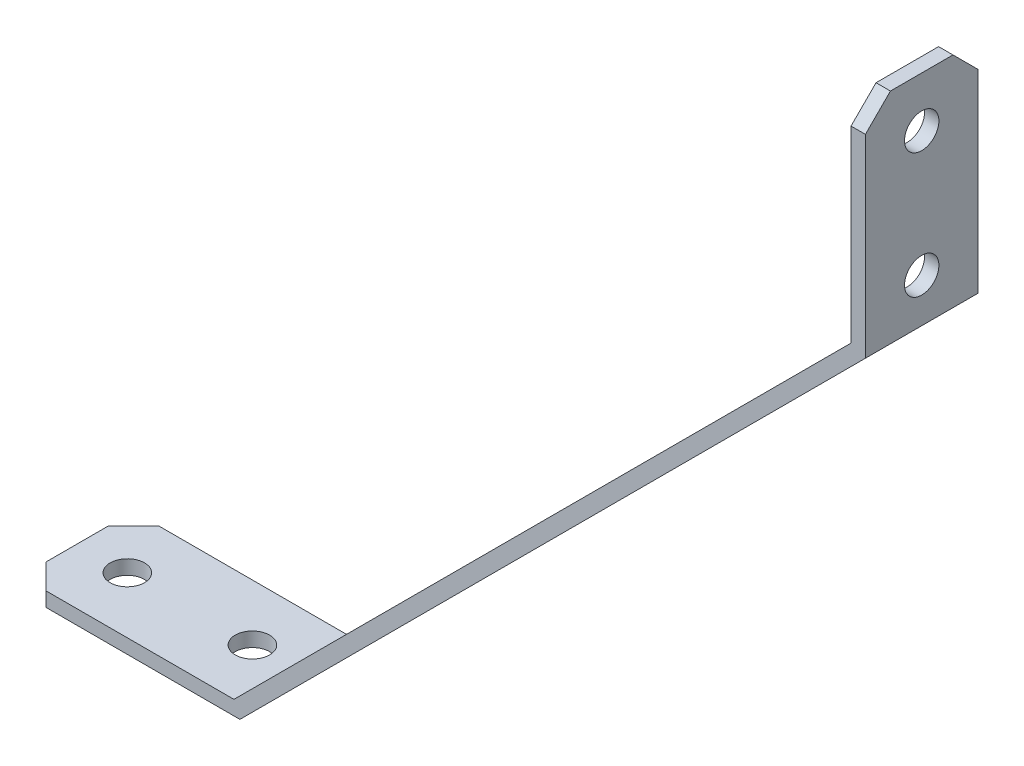
SolidWorks part; units mm, degrees
material "1023 Carbon Steel Sheet (SS)"
ref_plane "Front Plane" through (0, 0, 0) normal (0, 0, 1) x (1, 0, 0)
ref_plane "Top Plane" through (0, 0, 0) normal (0, 1, 0) x (1, 0, 0)
ref_plane "Right Plane" through (0, 0, 0) normal (1, 0, 0) x (0, 0, -1)
sketch "Sketch1" plane through (0, 0, 0) normal (0, 0, 1) x (1, 0, 0)
  line L0 (0, 0) -> (35, 0)
  line L1 (35, 0) -> (135, 100)
  line L2 (135, 100) -> (135, 135)
  line L3 (135, 135) -> (132.7, 135)
  line L4 (132.7, 135) -> (132.7, 100.9527)
  line L5 (132.7, 100.9527) -> (34.0473, 2.3)
  line L6 (34.0473, 2.3) -> (0, 2.3)
  line L7 (0, 2.3) -> (0, 0)
  dimension "D1" = 2.3
  dimension "D2" = 2.3
  dimension "D3" = 35
  dimension "D4" = 2.3
  dimension "D5" = 35
  dimension "D6" = 100
  dimension "D7" = 100
extrude "Boss-Extrude1" add sketch "Sketch1" along normal blind 18
sketch "Sketch2" plane through (132.7, 0, 0) normal (-1, 0, 0) x (0, 0, 1)
  line L0 (9, 135) -> (9, 100.9527) construction
  line L1 (18, 135) -> (0, 135) construction
  line L2 (18, 100.9527) -> (0, 100.9527) construction
  circle A0 centre (9, 127) radius 2.75
  circle A1 centre (9, 107) radius 2.75
  dimension "D1" = 5.5
  dimension "D2" = 27
  dimension "D3" = 7
extrude "Cut-Extrude1" cut sketch "Sketch2" against normal through all
chamfer "Chamfer1" distance 4 angle 45 2 edges at (133.85, 135, 18) (133.85, 135, 0)
sketch "Sketch3" plane through (0, 0, 0) normal (0, -1, 0) x (1, 0, 0)
  line L0 (35, 9) -> (0, 9) construction
  line L1 (35, 18) -> (35, 0) construction
  line L2 (0, 18) -> (0, 0) construction
  circle A0 centre (8, 9) radius 2.75
  circle A1 centre (28, 9) radius 2.75
  dimension "D1" = 5.5
  dimension "D2" = 27
  dimension "D3" = 7
extrude "Cut-Extrude2" cut sketch "Sketch3" against normal through all
chamfer "Chamfer2" distance 4 angle 45 2 edges at (0, 1.15, 0) (0, 1.15, 18)
